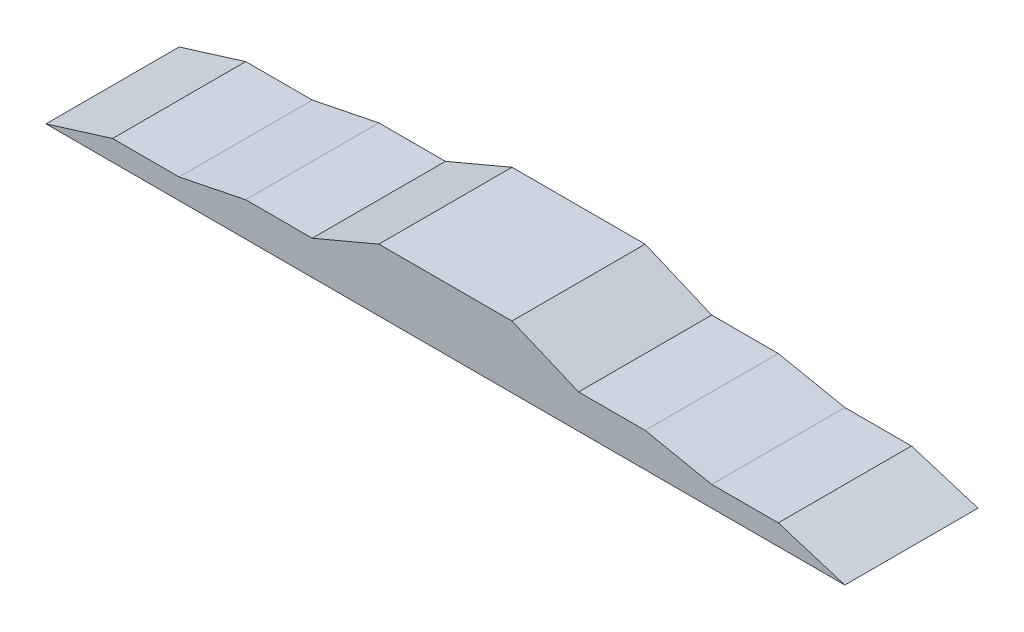
SolidWorks part; units mm, degrees
ref_plane "前视基准面" through (0, 0, 0) normal (0, 0, 1) x (1, 0, 0)
ref_plane "上视基准面" through (0, 0, 0) normal (0, 1, 0) x (1, 0, 0)
ref_plane "右视基准面" through (0, 0, 0) normal (1, 0, 0) x (0, 0, -1)
other "Configuration Table"
sketch "草图1" plane through (0, 0, 0) normal (0, 0, 1) x (1, 0, 0)
  line L0 (0, 0) -> (0, 77.2574) construction
  line L1 (0, 0) -> (-171.8763, 0) construction
  line L11 (-200, 15.4668) -> (-150, 25.6023)
  line L12 (-150, 25.6023) -> (-100, 25.6023)
  line L13 (-100, 25.6023) -> (-50, 46.742)
  line L14 (-200, 15.4668) -> (-250, 15.4668)
  line L15 (-250, 15.4668) -> (-300, 0)
  line L16 (-50, 46.742) -> (50, 46.742)
  line L17 (-300, 0) -> (300, 0)
  line L18 (250, 15.4668) -> (300, 0)
  line L19 (200, 15.4668) -> (250, 15.4668)
  line L20 (100, 25.6023) -> (50, 46.742)
  line L21 (150, 25.6023) -> (100, 25.6023)
  line L22 (200, 15.4668) -> (150, 25.6023)
  point P8 (0, 0)
  point P16 (0, 46.742)
  dimension "D1" = 50
  dimension "D2" = 11.459
  dimension "D3" = 17.189
  dimension "D4" = 50
  dimension "D5" = 50
  dimension "D6" = 50
  dimension "D7" = 50
  dimension "D8" = 50
  dimension "D9" = 22.918
extrude "凸台-拉伸1" add sketch "草图1" along normal blind 100
